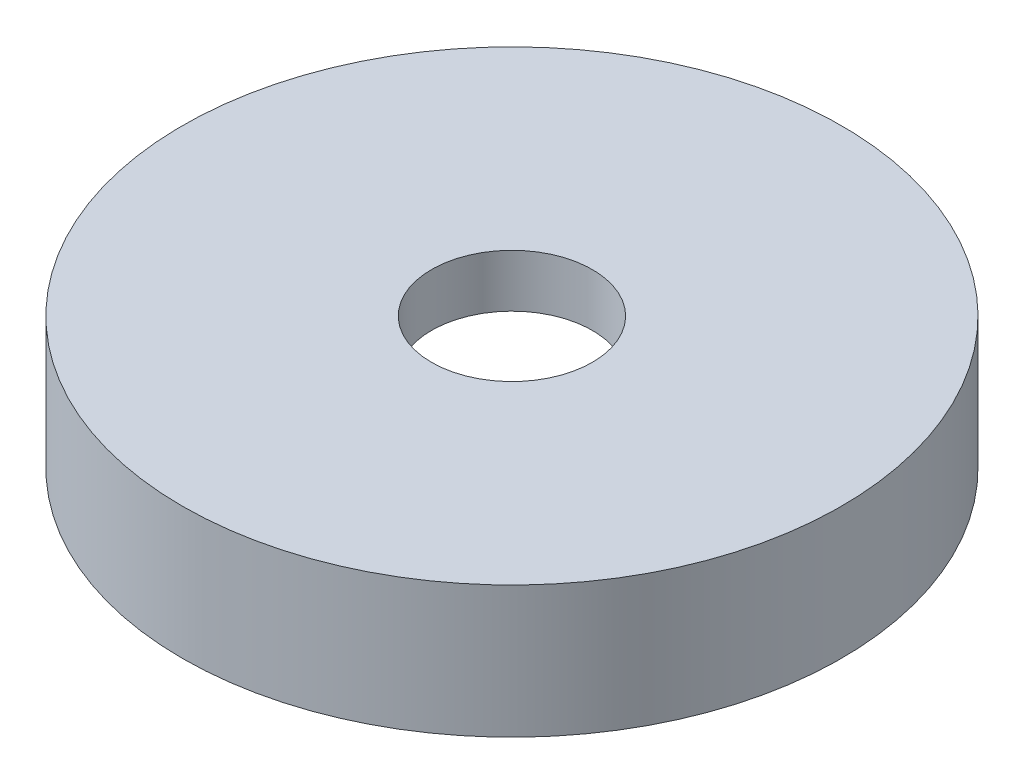
SolidWorks part; units mm, degrees
ref_plane "Front Plane" through (0, 0, 0) normal (0, 0, 1) x (1, 0, 0)
ref_plane "Top Plane" through (0, 0, 0) normal (0, 1, 0) x (1, 0, 0)
ref_plane "Right Plane" through (0, 0, 0) normal (1, 0, 0) x (0, 0, -1)
sketch "Sketch1" plane through (0, 0, 0) normal (0, 1, 0) x (1, 0, 0)
  line L1 (9.9304, 0) -> (4.9652, 8.6)
  line L2 (4.9652, 8.6) -> (-4.9652, 8.6)
  line L3 (-4.9652, 8.6) -> (-9.9304, 0)
  line L4 (-9.9304, 0) -> (-4.9652, -8.6)
  line L5 (-4.9652, -8.6) -> (4.9652, -8.6)
  line L6 (4.9652, -8.6) -> (9.9304, 0)
  circle A0 centre (0, 0) radius 8.6 construction
  circle A1 centre (0, 0) radius 12.5
  dimension "D2" = 25
  dimension "D1" = 17.2
extrude "Boss-Extrude1" add sketch "Sketch1" along normal blind 3
sketch "Sketch2" plane through (0, 3, 0) normal (0, 1, 0) x (1, 0, 0)
  circle A0 centre (0, 0) radius 3.05
  circle A1 centre (0, 0) radius 12.5
  dimension "D1" = 6.1
extrude "Boss-Extrude2" add sketch "Sketch2" along normal blind 2
